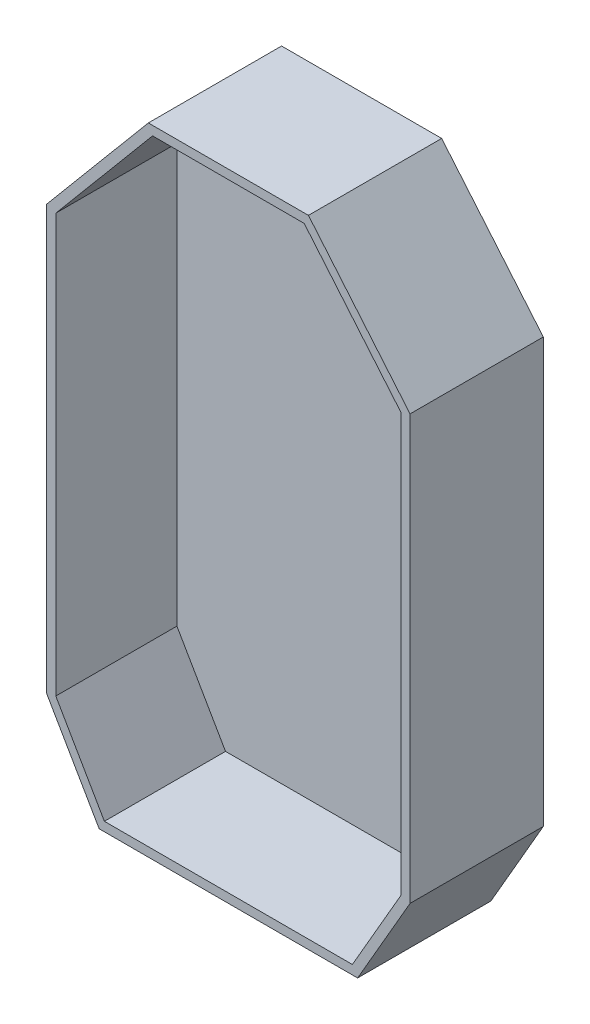
SolidWorks part; units mm, degrees
ref_plane "Front Plane" through (0, 0, 0) normal (0, 0, 1) x (1, 0, 0)
ref_plane "Top Plane" through (0, 0, 0) normal (0, 1, 0) x (1, 0, 0)
ref_plane "Right Plane" through (0, 0, 0) normal (1, 0, 0) x (0, 0, -1)
sketch "Sketch1" plane through (0, 0, 0) normal (0, 0, 1) x (1, 0, 0)
  line L0 (-60, 70) -> (-26.436, 110)
  line L2 (-60, 70) -> (-60, -70)
  line L5 (-26.436, 110) -> (26.436, 110)
  line L8 (42.6795, -100) -> (-42.6795, -100)
  line L9 (-42.6795, -100) -> (-60, -70)
  line L11 (0, -24.2) -> (0, 24.2) construction
  line L12 (42.6795, -100) -> (60, -70)
  line L13 (60, 70) -> (26.436, 110)
  line L14 (60, 70) -> (60, -70)
  point P4 (0, 110)
  point P5 (0, 0)
  point P8 (60, 0)
  dimension "D1" = 140
  dimension "D2" = 40
  dimension "D3" = 30
  dimension "D4" = 150
  dimension "D5" = 140
  dimension "D6" = 60
extrude "Boss-Extrude1" add sketch "Sketch1" along normal blind 4
sketch "Sketch2" plane through (0, 0, 4) normal (0, 0, 1) x (1, 0, 0)
  line L0 (-26.436, 110) -> (-60, 70)
  line L1 (-60, 70) -> (-60, -70)
  line L2 (-60, -70) -> (-42.6795, -100)
  line L3 (-42.6795, -100) -> (42.6795, -100)
  line L4 (42.6795, -100) -> (60, -70)
  line L5 (60, -70) -> (60, 70)
  line L6 (60, 70) -> (26.436, 110)
  line L7 (26.436, 110) -> (-26.436, 110)
  line L8 (-25.0371, 107) -> (-57, 68.9081)
  line L9 (-57, 68.9081) -> (-57, -69.1962)
  line L10 (-57, -69.1962) -> (-40.9474, -97)
  line L11 (-40.9474, -97) -> (40.9474, -97)
  line L12 (40.9474, -97) -> (57, -69.1962)
  line L13 (57, -69.1962) -> (57, 68.9081)
  line L14 (57, 68.9081) -> (25.0371, 107)
  line L15 (25.0371, 107) -> (-25.0371, 107)
  dimension "D1" = 3
extrude "Boss-Extrude2" add sketch "Sketch2" along normal blind 40
